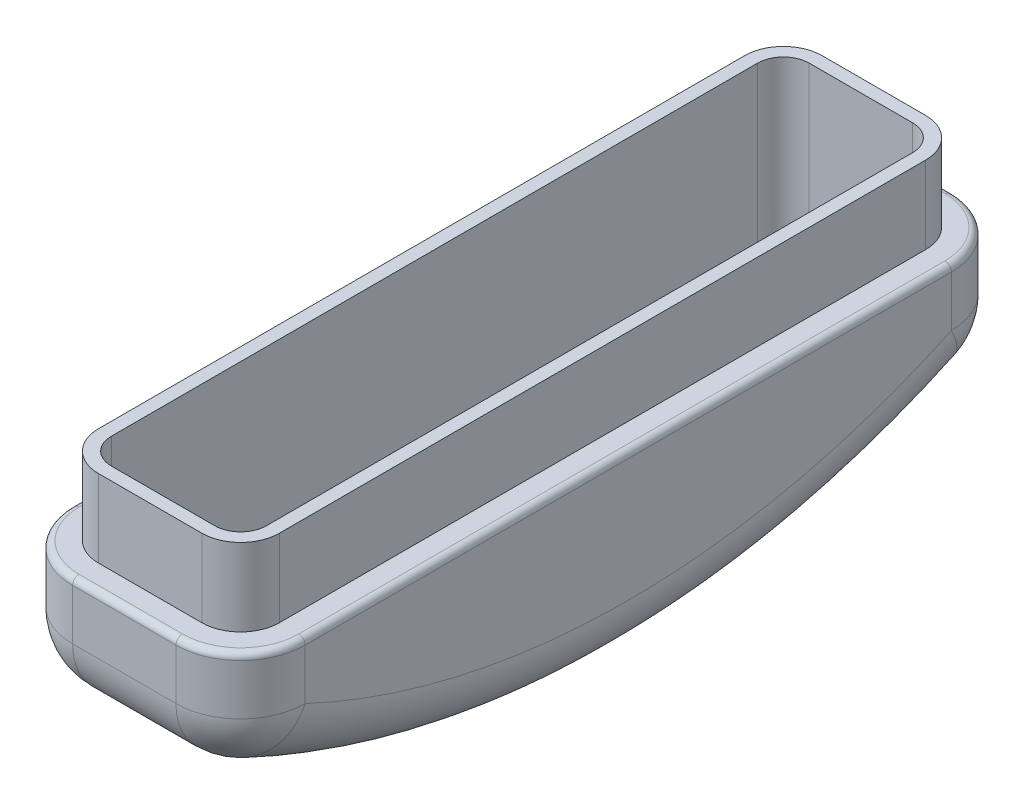
SolidWorks part; units mm, degrees
material "6061-T6 (SS)"
ref_plane "Front Plane" through (0, 0, 0) normal (1, 0, 0) x (0, 1, 0)
ref_plane "Top Plane" through (0, 0, 0) normal (0, 0, 1) x (0, 1, 0)
ref_plane "Right Plane" through (0, 0, 0) normal (0, 1, 0) x (-1, 0, 0)
sketch "Sketch1" plane through (0, 0, 0) normal (1, 0, 0) x (0, 1, 0)
  line L0 (0, 51.5798) -> (0, -35.0812) construction
  line L1 (-33.743, 0) -> (49.792, 0) construction
  line L2 (-15, 46.8019) -> (-15, -31.0125) construction
  line L3 (0, 30) -> (-7.5, 30)
  line L4 (-15, 0) -> (-15, -30) construction
  line L5 (-7.5, -30) -> (0, -30)
  line L6 (0, -30) -> (0, 30)
  line L7 (0, 28) -> (5, 28)
  line L8 (5, 28) -> (5, -28)
  line L9 (5, -28) -> (0, -28)
  line L10 (-15, 30) -> (-15, 0) construction
  line L11 (-7.5, 30) -> (-15, 30) construction
  line L12 (-15, -30) -> (-7.5, -30) construction
  arc A0 (-7.5, 30) -> (-7.5, -30) centre (48.75, 0) ccw
  point P11 (0, 0)
  point P16 (5, 0)
  dimension "D5" = 63.75
  dimension "D1" = 15
  dimension "D2" = 60
  dimension "D3" = 56
  dimension "D4" = 5
extrude "Boss-Extrude1" add sketch "Sketch1" along normal mid plane 18 contours L3 A0 L5 L6
shell "Shell2" thickness 3
sketch "Sketch3" plane through (0, 0, 0) normal (0, 1, 0) x (-1, 0, 0)
  line L18 (6, -27) -> (6, 27)
  line L19 (-6, -27) -> (6, -27)
  line L20 (-6, 27) -> (-6, -27)
  line L21 (6, 27) -> (-6, 27)
  line L22 (7, 28) -> (7, -28)
  line L23 (-7, -28) -> (7, -28)
  line L24 (-7, -28) -> (-7, 28)
  line L25 (-7, 28) -> (7, 28)
  point P3 (6, 0)
  point P5 (0, -27)
  point P6 (-7, 0)
  point P7 (0, 28)
  dimension "D2" = 1
  dimension "D1" = 1
  dimension "D3" = 56
  dimension "D4" = 14
extrude "Boss-Extrude3" add sketch "Sketch3" along normal mid plane 12
fillet "Fillet1" radius 5 2 edges at (0, -7.5, -30) (0, -7.5, 30)
fillet "Fillet5" radius 5 10 edges at (-9, -2.2077, 30) (-9, -7.0951, 29.2213) (-9, -2.2077, -30) (-9, -7.0951, -29.2213) (9, -2.2077, 30) (9, -7.0951, 29.2213) (9, -2.2077, -30) (9, -7.0951, -29.2213) (-9, -15, 0) (9, -15, 0)
fillet "Fillet8" radius 0.5 8 edges at (7.5355, 0, -28.5355) (0, 0, -30) (-7.5355, 0, -28.5355) (-9, 0, 0) (-7.5355, 0, 28.5355) (0, 0, 30) (7.5355, 0, 28.5355) (9, 0, 0)
fillet "Fillet9" radius 3 4 edges at (-7, 3, 28) (-7, 3, -28) (7, 3, -28) (7, 3, 28)
fillet "Fillet10" radius 2 4 edges at (-6, 0.1649, -27) (-6, 0.1649, 27) (6, 0.1649, -27) (6, 0.1649, 27)
